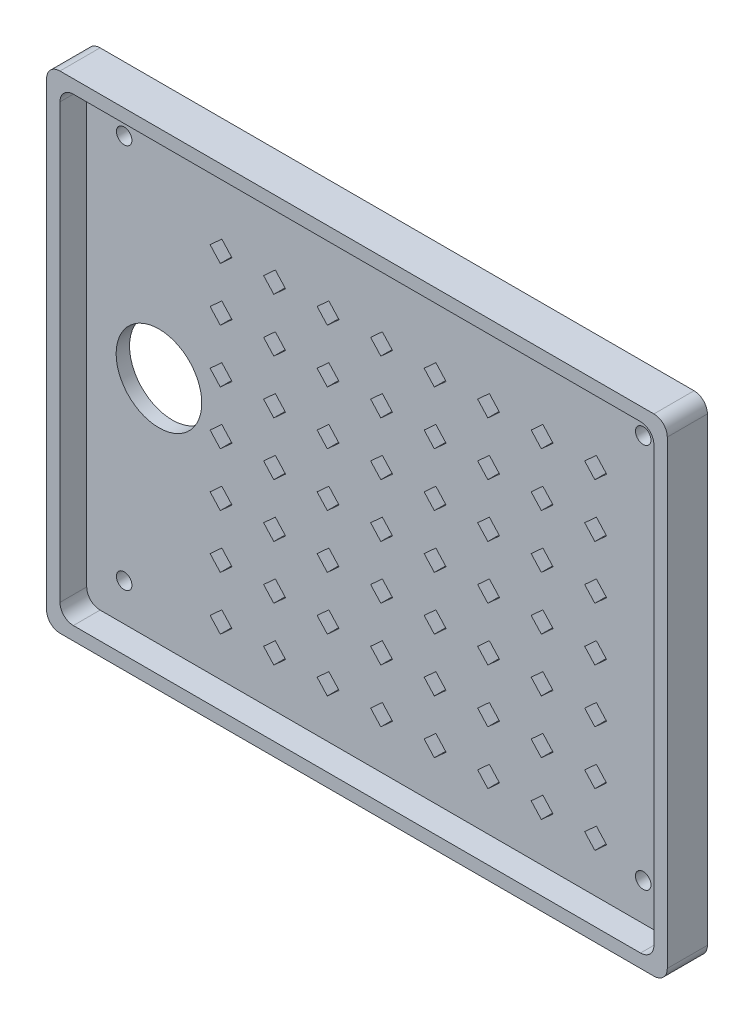
SolidWorks part; units mm, degrees
ref_plane "Front Plane" through (0, 0, 0) normal (0, 0, 1) x (1, 0, 0)
ref_plane "Top Plane" through (0, 0, 0) normal (0, 1, 0) x (1, 0, 0)
ref_plane "Right Plane" through (0, 0, 0) normal (1, 0, 0) x (0, 0, -1)
sketch "Sketch1" plane through (0, 0, 0) normal (0, 0, 1) x (1, 0, 0)
  line L1 (-58, 45.5) -> (58, 45.5)
  line L2 (-58, 45.5) -> (-58, -45.5)
  line L3 (-58, -45.5) -> (58, -45.5)
  line L4 (58, 45.5) -> (58, -45.5)
  dimension "D1" = 116
  dimension "D2" = 91
  dimension "D3" = 58
  dimension "D4" = 45.5
extrude "Lid Extrude" add sketch "Sketch1" along normal blind 2.5
sketch "Sketch3" plane through (0, 0, 2.5) normal (0, 0, 1) x (1, 0, 0)
  line L0 (58, -45.5) -> (58, 45.5) construction
  line L1 (-58, 45.5) -> (58, 45.5)
  line L2 (-58, 45.5) -> (-58, 43)
  line L3 (-58, 43) -> (58, 43)
  line L4 (58, 45.5) -> (58, 43)
  line L5 (-58, -45.5) -> (58, -45.5) construction
  line L6 (-58, 45.5) -> (-55.5, 45.5)
  line L7 (-58, 45.5) -> (-58, -45.5)
  line L8 (-58, -45.5) -> (-55.5, -45.5)
  line L9 (-55.5, 45.5) -> (-55.5, -45.5)
  line L11 (-58, -45.5) -> (58, -45.5)
  line L12 (-58, -45.5) -> (-58, -43)
  line L13 (-58, -43) -> (58, -43)
  line L14 (58, -45.5) -> (58, -43)
  line L15 (58, -45.5) -> (55.5, -45.5)
  line L16 (58, -45.5) -> (58, 45.5)
  line L17 (58, 45.5) -> (55.5, 45.5)
  line L18 (55.5, -45.5) -> (55.5, 45.5)
  dimension "D1" = 2.5
  dimension "D2" = 2.5
  dimension "D3" = 2.5
  dimension "D4" = 2.5
extrude "Rails" add sketch "Sketch3" along normal blind 5 contours L3 L18 L1 L9 | L9 L1 L2 L3 | L7 L13 L9 L3 | L13 L7 L8 L9 | L11 L18 L13 L9 | L18 L11 L14 L13 | L18 L13 L16 L3 | L18 L3 L4 L1
fillet "Edge Fillets" radius 2.5 8 edges at (-58, -45.5, 3.75) (-55.5, -43, 5) (58, -45.5, 3.75) (55.5, -43, 5) (55.5, 43, 5) (58, 45.5, 3.75) (-55.5, 43, 5) (-58, 45.5, 3.75)
sketch "Sketch5" plane through (0, 0, 0) normal (0, 0, -1) x (-1, 0, 0)
  line L6 (58, 43) -> (58, -43) construction
  line L7 (55.5, -45.5) -> (-55.5, -45.5) construction
  circle A0 centre (42, 0) radius 8
  point P8 (42, 0)
  dimension "D5" = 16
  dimension "D6" = 45.5
extrude "Button Hole" cut sketch "Sketch5" against normal blind 5
sketch "Sketch2" plane through (0, 0, 2.5) normal (0, 0, 1) x (1, 0, 0)
  line L0 (-58, 45.5) -> (-58, -45.5) construction
  line L1 (-58, -45.5) -> (58, -45.5) construction
  line L7 (-32.4422, -33.5794) -> (-30.25, -31.5794)
  line L8 (-30.25, -31.5794) -> (-28.3437, -33.6689)
  line L9 (-28.3437, -33.6689) -> (-30.5358, -35.6689)
  line L10 (-30.5358, -35.6689) -> (-32.4422, -33.5794)
  point P5 (-33, -35.5)
  dimension "D3" = 2
  dimension "D4" = 2
  dimension "D5" = 2.8284
  dimension "D6" = 25
  dimension "D7" = 10
extrude "Lid Airflow Hole" cut sketch "Sketch2" against normal blind 5
pattern_linear "Airflow Pattern" count 8 spacing 10 along (1, 0, 0) count 7 spacing 10 along (0, 1, 0) of "Lid Airflow Hole"
sketch "Sketch6" plane through (0, 0, 0) normal (0, 0, -1) x (-1, 0, 0)
  line L0 (58, 43) -> (58, -43) construction
  line L1 (55.5, -45.5) -> (-55.5, -45.5) construction
  line L3 (-55.5, 45.5) -> (55.5, 45.5) construction
  line L4 (-58, -43) -> (-58, 43) construction
  circle A0 centre (48.5, -36) radius 1.45
  circle A2 centre (48.5, 36) radius 1.45
  circle A3 centre (-48.5, -36) radius 1.45
  circle A4 centre (-48.5, 36) radius 1.45
  point P0 (48.5, -36)
  point P7 (48.5, 36)
  point P11 (-48.5, -36)
  point P18 (-48.5, 36)
  dimension "D3" = 9.5
  dimension "D5" = 9.5
  dimension "D7" = 9.5
  dimension "D9" = 2.9
  dimension "D1" = 9.5
  dimension "D2" = 9.5
  dimension "D4" = 9.5
  dimension "D6" = 9.5
  dimension "D8" = 9.5
extrude "Mounting Holes" cut sketch "Sketch6" against normal blind 2.5
